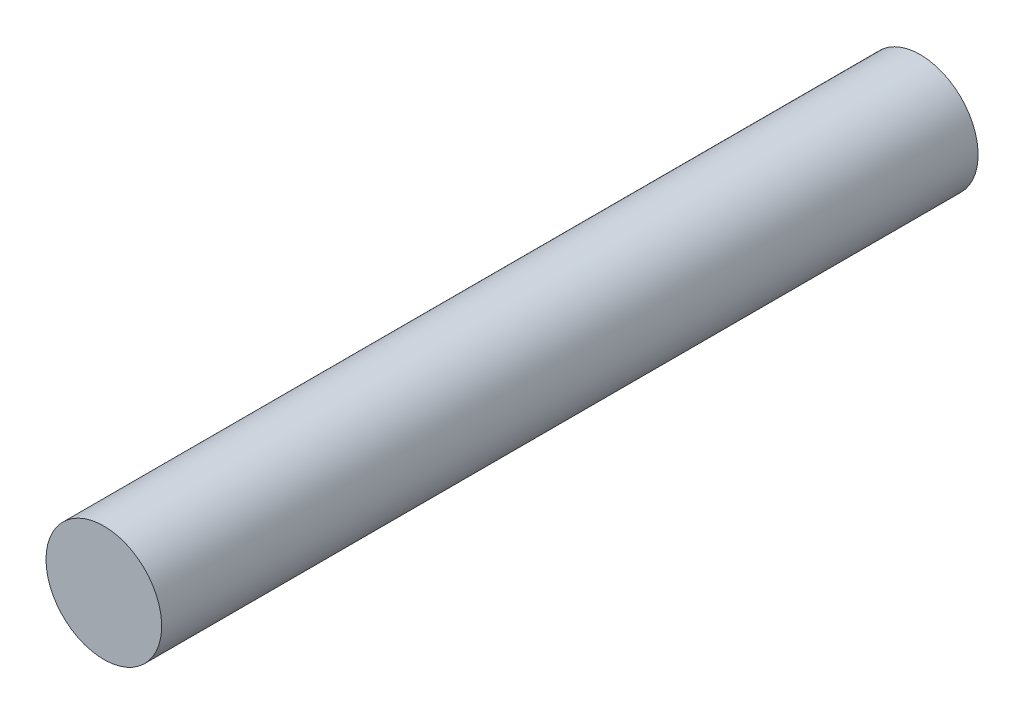
SolidWorks part; units mm, degrees
ref_plane "Front Plane" through (0, 0, 0) normal (0, 0, 1) x (1, 0, 0)
ref_plane "Top Plane" through (0, 0, 0) normal (0, 1, 0) x (1, 0, 0)
ref_plane "Right Plane" through (0, 0, 0) normal (1, 0, 0) x (0, 0, -1)
sketch "Sketch1" plane through (0, 0, 0) normal (0, 0, 1) x (1, 0, 0)
  circle A0 centre (0, 0) radius 4.25
  dimension "D1" = 8.5
extrude "Boss-Extrude1" add sketch "Sketch1" along normal blind 60
sketch "Sketch2" plane through (0, 0, 0) normal (0, 0, -1) x (-1, 0, 0)
  line L0 (0, 0) -> (0, 3) construction
  line L1 (1, 3) -> (-1, 3)
  circle A1 centre (-1, 3) radius 0.5
  circle A2 centre (1, 3) radius 0.5
  point P7 (0, 3)
  dimension "D1" = 1
  dimension "D2" = 1
  dimension "D3" = 2
  dimension "D4" = 3
extrude "Boss-Extrude2" add sketch "Sketch2" along normal blind 0.1
pattern_circular "CirPattern1" count 4 over 360 about axis through (0, 0, 0) along (0, 0, 1) of "Boss-Extrude2"
